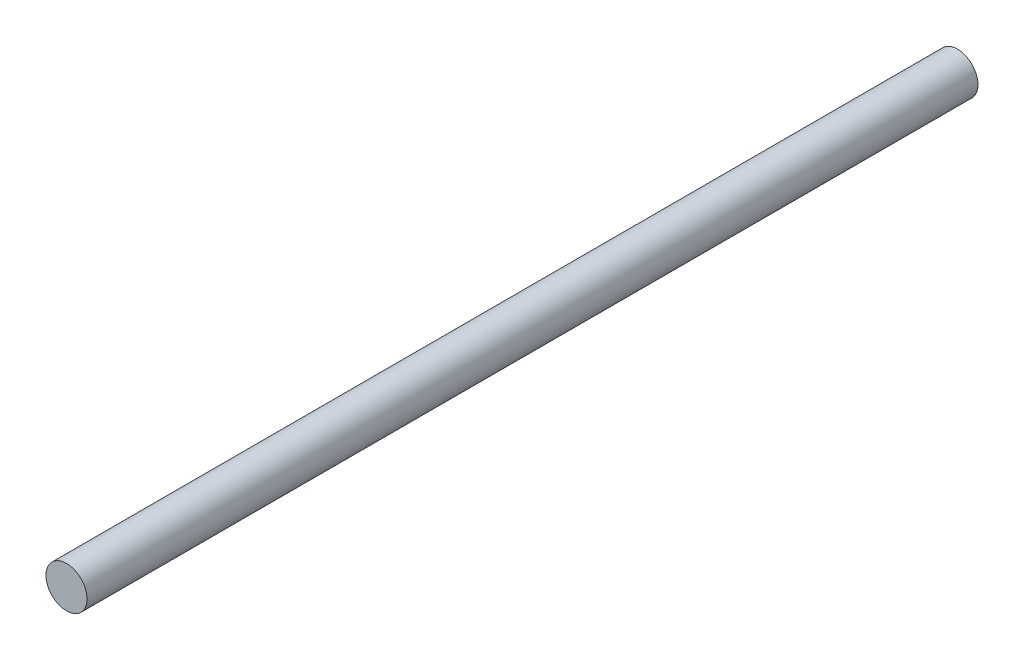
SolidWorks part; units mm, degrees
ref_plane "Front Plane" through (0, 0, 0) normal (0, 0, 1) x (1, 0, 0)
ref_plane "Top Plane" through (0, 0, 0) normal (0, 1, 0) x (1, 0, 0)
ref_plane "Right Plane" through (0, 0, 0) normal (1, 0, 0) x (0, 0, -1)
sketch "Sketch1" plane through (0, 0, 0) normal (0, 0, 1) x (1, 0, 0)
  circle A0 centre (0, 0) radius 3
extrude "Boss-Extrude1" add sketch "Sketch1" along normal blind 130
